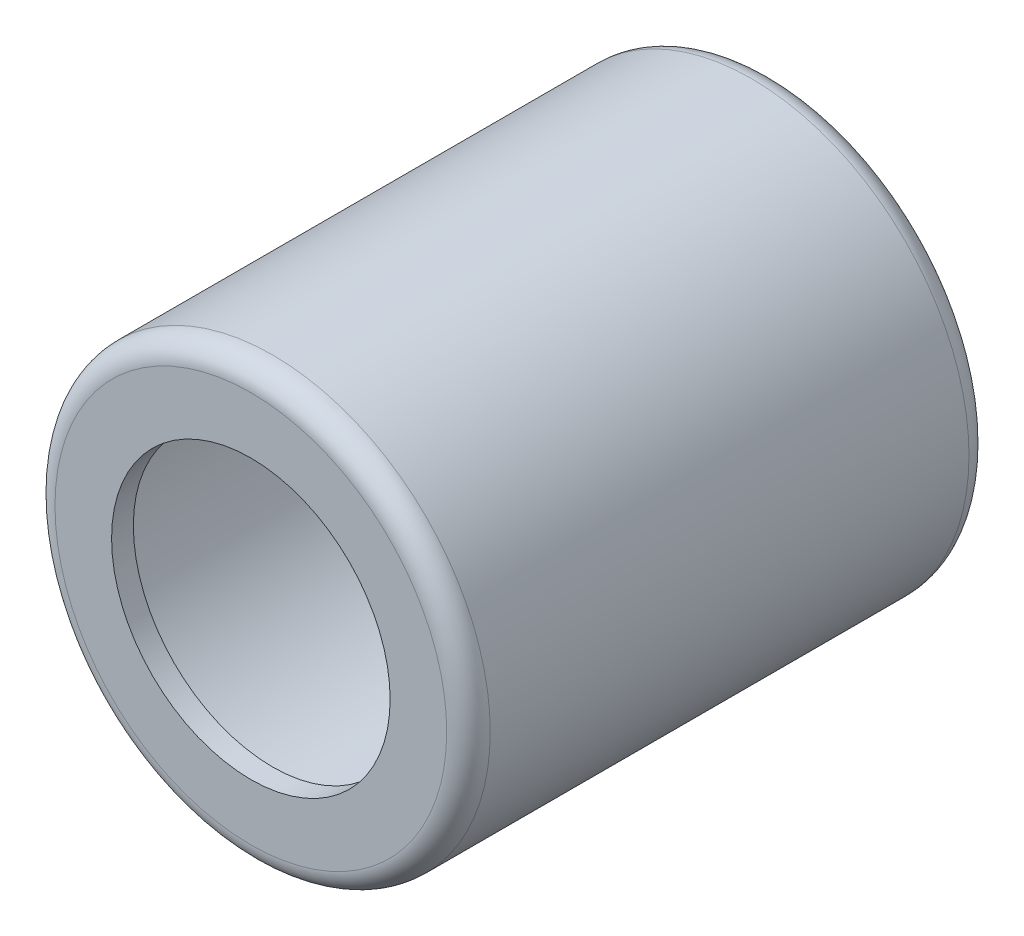
SolidWorks part; units mm, degrees
ref_plane "前视基准面" through (0, 0, 0) normal (0, 0, 1) x (1, 0, 0)
ref_plane "上视基准面" through (0, 0, 0) normal (0, 1, 0) x (1, 0, 0)
ref_plane "右视基准面" through (0, 0, 0) normal (1, 0, 0) x (0, 0, -1)
sketch "草图1" plane through (0, 0, 0) normal (0, 1, 0) x (1, 0, 0)
  line L0 (0, -32.4033) -> (0, 41.6883) construction
  line L1 (-44.8135, 0) -> (47.9403, 0) construction
  line L2 (3.2, -6) -> (5, -6)
  line L3 (5, -6) -> (5, 6)
  line L4 (5, 6) -> (3.2, 6)
  line L5 (3.2, 6) -> (3.2, 5.5)
  line L6 (3.2, -5.5) -> (4.5, -5.5)
  line L7 (4.5, -5.5) -> (4.5, 5.5)
  line L8 (4.5, 5.5) -> (3.2, 5.5)
  line L9 (3.2, -5.5) -> (3.2, -6)
  dimension "D1" = 5
  dimension "D2" = 12
  dimension "D3" = 3.2
  dimension "D4" = 0.5
  dimension "D5" = 11
revolve "旋转1" add sketch "草图1" angle 360 about L0
fillet "圆角1" radius 0.3 2 edges at (4.5, 0, -5.5) (4.5, 0, 5.5)
fillet "圆角2" radius 0.5 1 edges at (5, 0, 6)
fillet "圆角3" radius 0.5 1 edges at (5, 0, -6)
